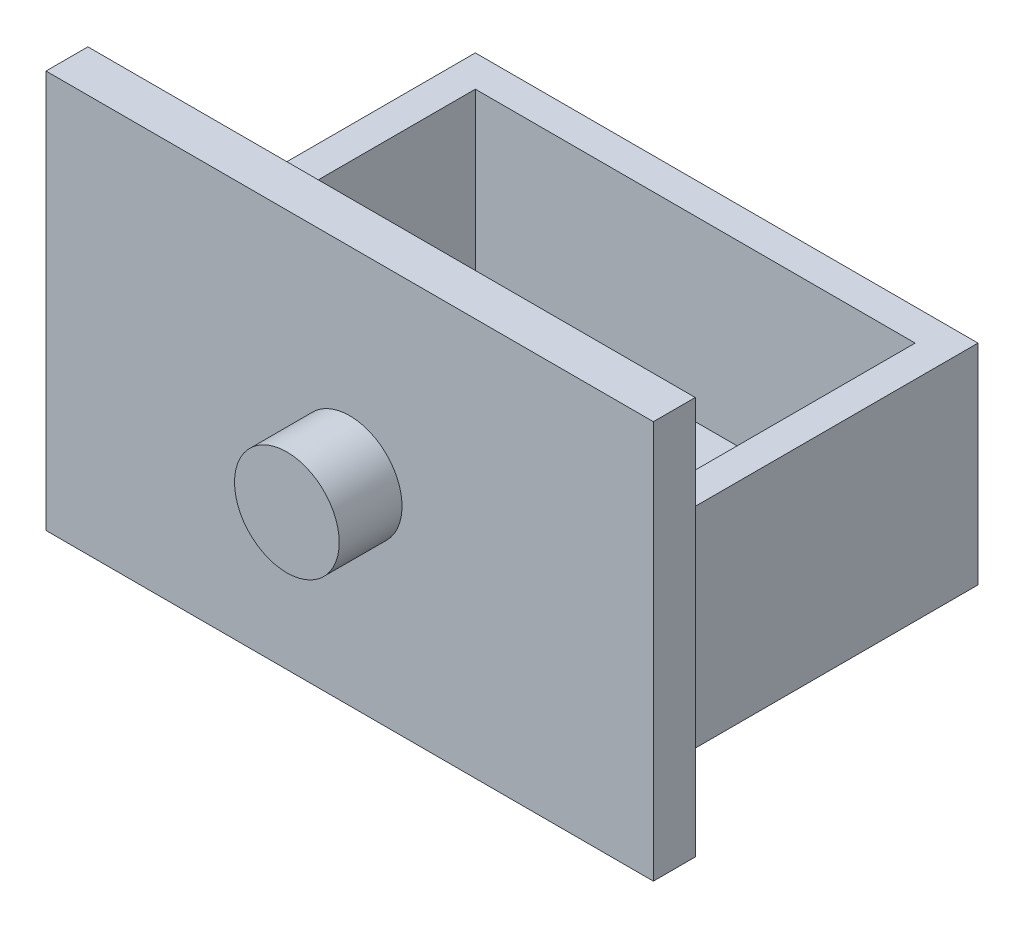
SolidWorks part; units mm, degrees
ref_plane "前视基准面" through (0, 0, 0) normal (0, 0, 1) x (1, 0, 0)
ref_plane "上视基准面" through (0, 0, 0) normal (0, 1, 0) x (1, 0, 0)
ref_plane "右视基准面" through (0, 0, 0) normal (1, 0, 0) x (0, 0, -1)
sketch "草图2" plane through (0, 0, 0) normal (0, 0, 1) x (1, 0, 0)
  line L1 (-14.5, -9.5) -> (14.5, -9.5)
  line L2 (-14.5, -9.5) -> (-14.5, 9.5)
  line L3 (-14.5, 9.5) -> (14.5, 9.5)
  line L4 (14.5, -9.5) -> (14.5, 9.5)
  line L5 (-14.5, -9.5) -> (14.5, 9.5) construction
  line L6 (-14.5, 9.5) -> (14.5, -9.5) construction
  point P0 (0, 0)
  dimension "D1" = 29
  dimension "D2" = 19
extrude "凸台-拉伸1" add sketch "草图2" along normal blind 2
sketch "草图3" plane through (0, 0, 0) normal (0, 0, -1) x (-1, 0, 0)
  line L0 (14.5, -9.5) -> (-14.5, -9.5) construction
  line L5 (-12, 2.5) -> (12, 2.5)
  line L6 (-12, 2.5) -> (-12, -7.5)
  line L7 (-12, -7.5) -> (12, -7.5)
  line L8 (12, 2.5) -> (12, -7.5)
  point P7 (0, 2.5)
  dimension "D1" = 2
  dimension "D2" = 10
  dimension "D3" = 24
extrude "凸台-拉伸2" add sketch "草图3" along normal blind 16
sketch "草图4" plane through (0, 2.5, 0) normal (0, 1, 0) x (1, 0, 0)
  line L0 (-12, 0) -> (-12, 16) construction
  line L1 (-12, 16) -> (12, 16) construction
  line L2 (12, 16) -> (12, 0) construction
  line L3 (12, 0) -> (-12, 0) construction
  line L4 (-10.5, 14.5) -> (10.5, 14.5)
  line L5 (10.5, 14.5) -> (10.5, 1.5)
  line L6 (10.5, 1.5) -> (-10.5, 1.5)
  line L7 (-10.5, 1.5) -> (-10.5, 14.5)
  dimension "D1" = 1.5
extrude "切除-拉伸1" cut sketch "草图4" against normal blind 8.5
sketch "草图5" plane through (0, 0, 2) normal (0, 0, 1) x (1, 0, 0)
  circle A0 centre (0, 0) radius 2.5
  dimension "D1" = 5
extrude "凸台-拉伸3" add sketch "草图5" along normal blind 3
